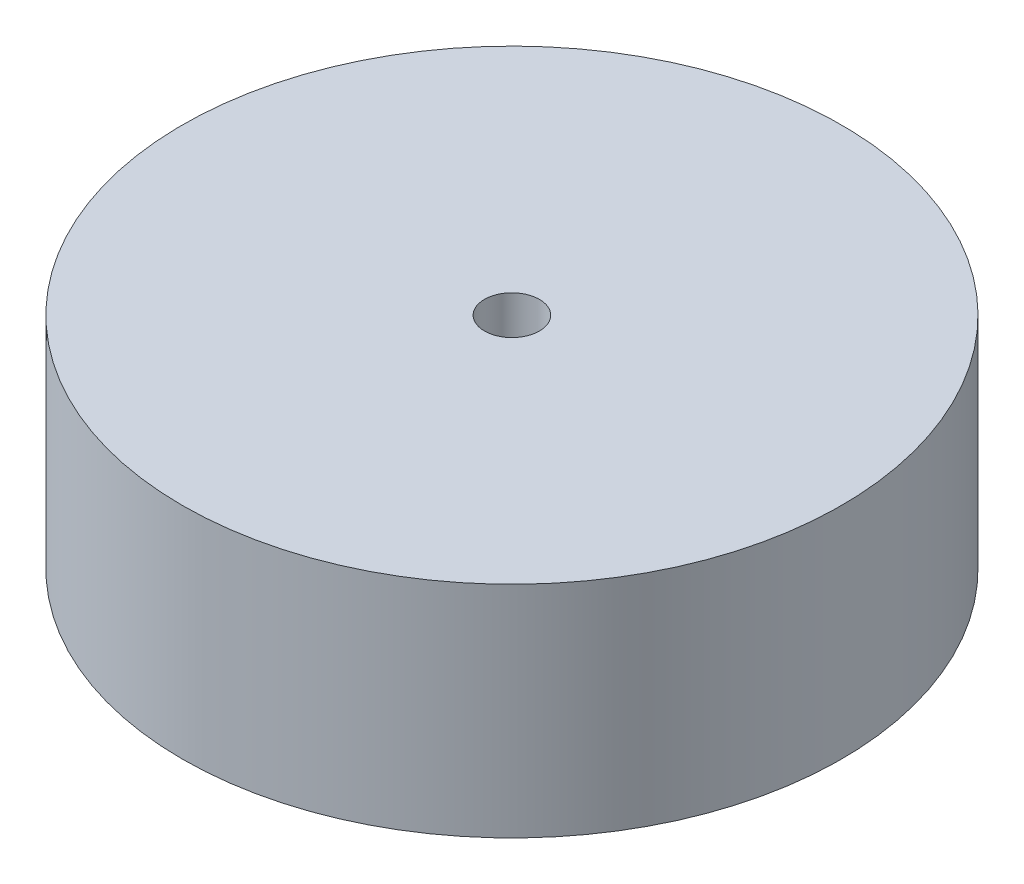
SolidWorks part; units mm, degrees
ref_plane "Front Plane" through (0, 0, 0) normal (0, 0, 1) x (1, 0, 0)
ref_plane "Top Plane" through (0, 0, 0) normal (0, 1, 0) x (1, 0, 0)
ref_plane "Right Plane" through (0, 0, 0) normal (1, 0, 0) x (0, 0, -1)
sketch "Sketch1" plane through (0, 0, 0) normal (0, 1, 0) x (1, 0, 0)
  circle A0 centre (0, 0) radius 19.05
  circle A1 centre (0, 0) radius 1.5875
  dimension "D1" = 38.1
  dimension "D2" = 3.175
extrude "Boss-Extrude1" add sketch "Sketch1" along normal blind 12.7
